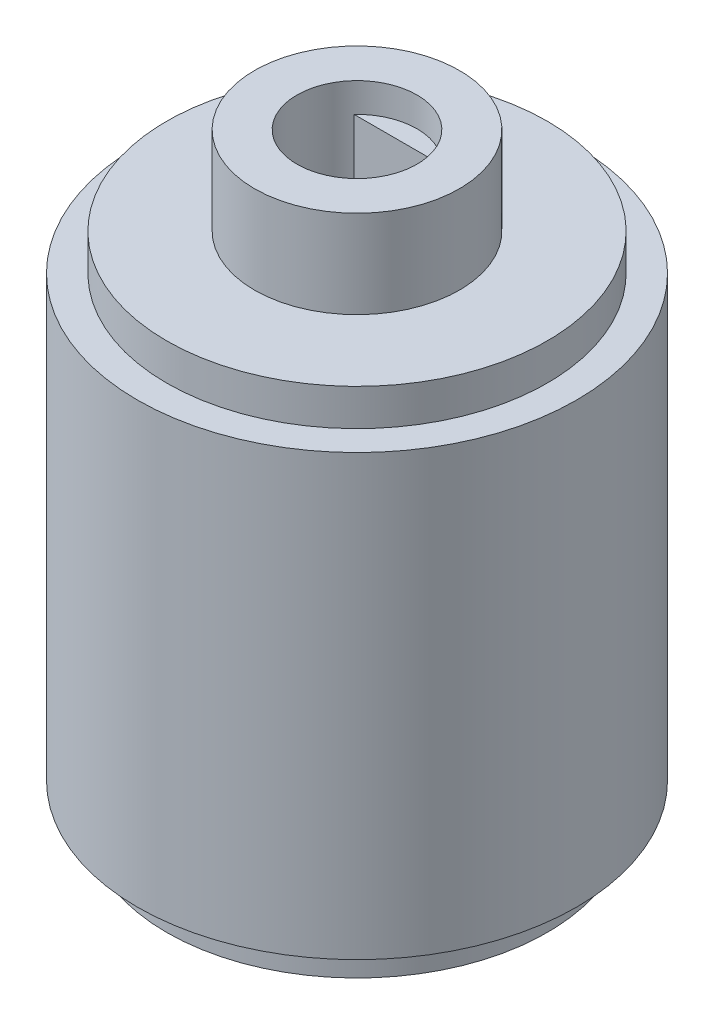
SolidWorks part; units mm, degrees
ref_plane "Front Plane" through (0, 0, 0) normal (0, 0, 1) x (1, 0, 0)
ref_plane "Top Plane" through (0, 0, 0) normal (0, 1, 0) x (1, 0, 0)
ref_plane "Right Plane" through (0, 0, 0) normal (1, 0, 0) x (0, 0, -1)
sketch "Sketch1" plane through (0, 0, 0) normal (0, 1, 0) x (1, 0, 0)
  circle A0 centre (0, 0) radius 15
  dimension "D1" = 30
extrude "Boss-Extrude1" add sketch "Sketch1" along normal blind 60
sketch "Sketch2" plane through (0, 60, 0) normal (0, 1, 0) x (1, 0, 0)
  circle A0 centre (0, 0) radius 13
  circle A1 centre (0, 0) radius 15
  circle A2 centre (0, 0) radius 15
  dimension "D2" = 26
  dimension "D1" = 0
extrude "Cut-Extrude1" cut sketch "Sketch2" against normal blind 2.5 contours A0
sketch "Sketch3" plane through (0, 0, 0) normal (0, -1, 0) x (1, 0, 0)
  circle A1 centre (0, 0) radius 15
  circle A2 centre (0, 0) radius 15
  dimension "D1" = 0
extrude "Cut-Extrude2" cut sketch "Sketch3" against normal blind 25
sketch "Sketch4" plane through (0, 25, 0) normal (0, -1, 0) x (1, 0, 0)
  circle A0 centre (0, 0) radius 13
  circle A1 centre (0, 0) radius 15
  circle A2 centre (0, 0) radius 15
  dimension "D2" = 26
  dimension "D1" = 0
extrude "Cut-Extrude3" cut sketch "Sketch4" against normal blind 2.5
sketch "Sketch6" plane through (0, 25, 0) normal (0, -1, 0) x (1, 0, 0)
  circle A0 centre (0, 0) radius 2.8705
extrude "Boss-Extrude2" add sketch "Sketch6" along normal blind 9.5
sketch "Sketch7" plane through (0, 60, 0) normal (0, 1, 0) x (1, 0, 0)
  circle A2 centre (0, 0) radius 7
  circle A3 centre (0, 0) radius 7
  dimension "D1" = 6
extrude "Boss-Extrude3" add sketch "Sketch7" along normal blind 2
sketch "Sketch8" plane through (0, 25, 0) normal (0, -1, 0) x (1, 0, 0)
  circle A2 centre (0, 0) radius 19
  circle A3 centre (0, 0) radius 19
  dimension "D1" = 6
extrude "Cut-Extrude4" cut sketch "Sketch8" along normal through all
sketch "Sketch9" plane through (0, 62, 0) normal (0, 1, 0) x (1, 0, 0)
  line L0 (0, -4.1) -> (0, 2.8) construction
  line L1 (0, 2.8) -> (-2.995, 2.8)
  line L2 (-2.995, 2.8) -> (2.995, 2.8)
  line L3 (0, 2.8) -> (2.995, 2.8)
  arc A0 (-2.995, 2.8) -> (2.995, 2.8) centre (0, 0) ccw
  dimension "D1" = 8.2
  dimension "D2" = 6.9
extrude "Cut-Extrude5" cut sketch "Sketch9" against normal through all contours L0 A0 L2 | A0 L0 L1
sketch "Sketch10" plane through (0, 62, 0) normal (0, 1, 0) x (1, 0, 0)
  circle A0 centre (0, 0) radius 7
extrude "Boss-Extrude4" add sketch "Sketch10" along normal blind 2
sketch "Sketch11" plane through (0, 25, 0) normal (0, -1, 0) x (1, 0, 0)
  line L2 (-2.995, -2.8) -> (2.995, -2.8)
  line L3 (-2.995, -2.8) -> (2.995, -2.8)
  arc A2 (2.995, -2.8) -> (-2.995, -2.8) centre (0, 0) ccw
  arc A3 (2.995, -2.8) -> (-2.995, -2.8) centre (0, 0) ccw
  dimension "D1" = 0
extrude "Cut-Extrude6" cut sketch "Sketch11" against normal through all
sketch "Sketch12" plane through (0, 64, 0) normal (0, 1, 0) x (1, 0, 0)
  circle A2 centre (0, 0) radius 7
  circle A3 centre (0, 0) radius 7
  dimension "D1" = 0
extrude "Boss-Extrude5" add sketch "Sketch12" along normal blind 2
sketch "Sketch13" plane through (0, 25, 0) normal (0, -1, 0) x (1, 0, 0)
  line L2 (-2.995, -2.8) -> (2.995, -2.8)
  line L3 (-2.995, -2.8) -> (2.995, -2.8)
  arc A2 (2.995, -2.8) -> (-2.995, -2.8) centre (0, 0) ccw
  arc A3 (2.995, -2.8) -> (-2.995, -2.8) centre (0, 0) ccw
  dimension "D1" = 0
extrude "Cut-Extrude7" cut sketch "Sketch13" against normal through all
sketch "Sketch14" plane through (0, 66, 0) normal (0, 1, 0) x (1, 0, 0)
  circle A0 centre (0, 0) radius 4.1
extrude "Cut-Extrude8" cut sketch "Sketch14" against normal blind 2
